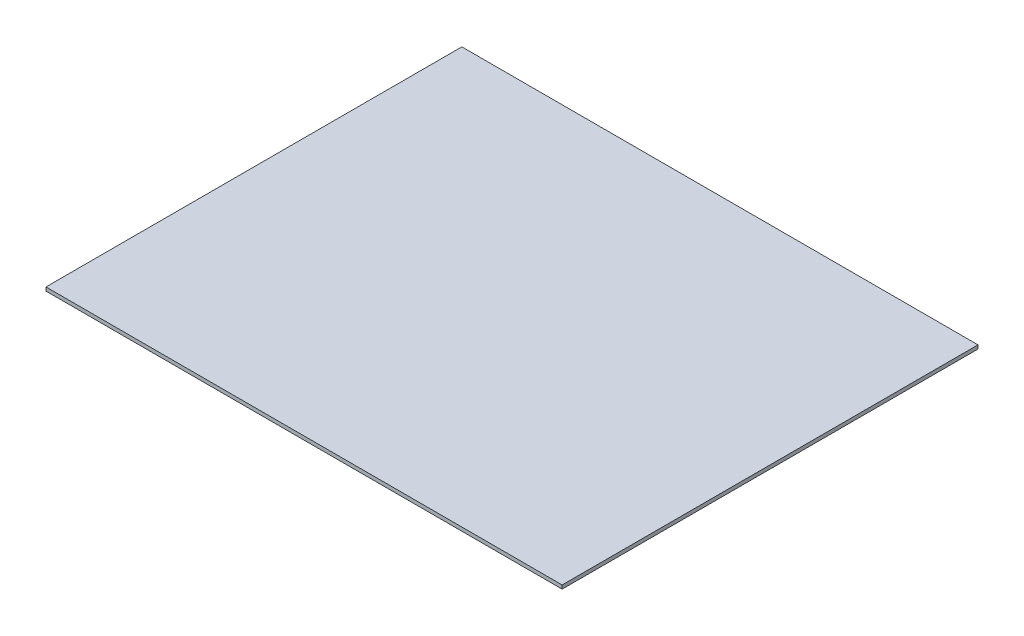
SolidWorks part; units mm, degrees
ref_plane "Front Plane" through (0, 0, 0) normal (0, 0, 1) x (1, 0, 0)
ref_plane "Top Plane" through (0, 0, 0) normal (0, 1, 0) x (1, 0, 0)
ref_plane "Right Plane" through (0, 0, 0) normal (1, 0, 0) x (0, 0, -1)
sketch "Sketch1" plane through (0, 0, 0) normal (0, 1, 0) x (1, 0, 0)
  line L1 (-123.5, 99.5) -> (123.5, 99.5)
  line L2 (-123.5, 99.5) -> (-123.5, -99.5)
  line L3 (-123.5, -99.5) -> (123.5, -99.5)
  line L4 (123.5, 99.5) -> (123.5, -99.5)
  line L5 (-123.5, 99.5) -> (123.5, -99.5) construction
  line L6 (-123.5, -99.5) -> (123.5, 99.5) construction
  point P0 (0, 0)
  dimension "D1" = 247
  dimension "D2" = 199
extrude "Shape" add sketch "Sketch1" along normal blind 1.75
